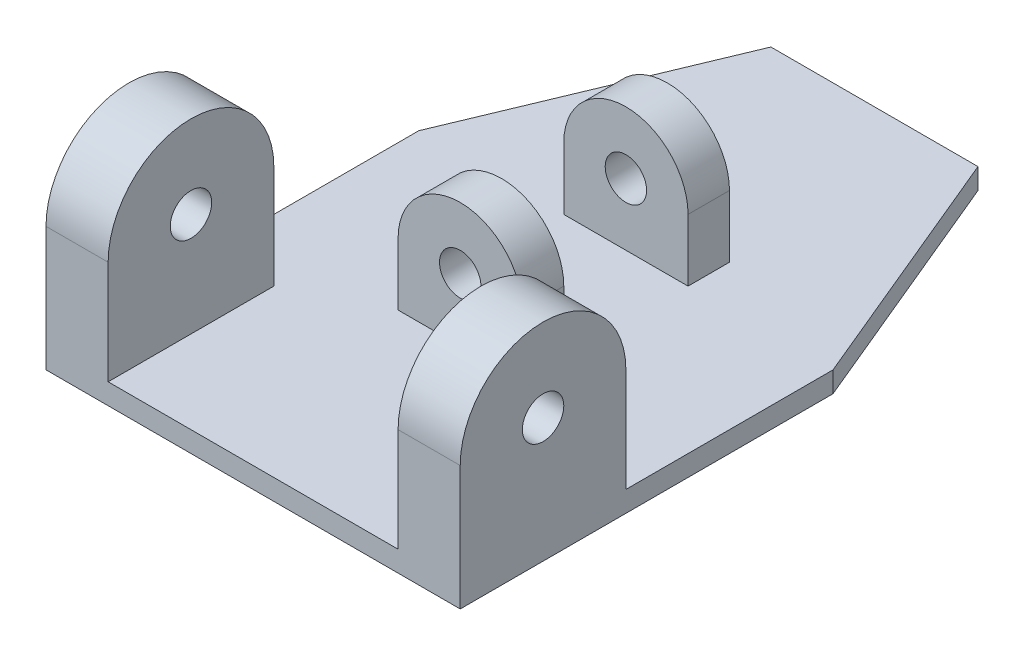
SolidWorks part; units mm, degrees
ref_plane "前视基准面" through (0, 0, 0) normal (0, 0, 1) x (1, 0, 0)
ref_plane "上视基准面" through (0, 0, 0) normal (0, 1, 0) x (1, 0, 0)
ref_plane "右视基准面" through (0, 0, 0) normal (1, 0, 0) x (0, 0, -1)
other "Configuration Table"
sketch "草图1" plane through (0, 0, 0) normal (0, 1, 0) x (1, 0, 0)
  line L0 (0, 0) -> (0, 255.8207) construction
  line L1 (-100, 0) -> (100, 0)
  line L2 (100, 0) -> (100, 180)
  line L3 (100, 180) -> (50, 300)
  line L4 (50, 300) -> (-50, 300)
  line L5 (-100, 180) -> (-50, 300)
  line L6 (-100, 0) -> (-100, 180)
  point P8 (0, 300)
  dimension "D1" = 300
  dimension "D2" = 100
  dimension "D3" = 120
  dimension "D4" = 50
extrude "凸台-拉伸1" add sketch "草图1" along normal blind 10
sketch "草图2" plane through (100, 0, 0) normal (1, 0, 0) x (0, 0, -1)
  line L0 (40, 100) -> (40, -10.3339) construction
  line L1 (0, 10) -> (0, 0) construction
  line L2 (0, 10) -> (0, 60)
  line L3 (80, 10) -> (80, 60)
  arc A0 (80, 60) -> (0, 60) centre (40, 60) ccw
  circle A1 centre (40, 60) radius 10
  line M6 (180, 10) -> (0, 10)
  dimension "D3" = 20
  dimension "D1" = 40
  dimension "D2" = 50
extrude "凸台-拉伸2" add sketch "草图2" against normal up to surface (200 mm away) contours A0 L0 A1 L3 M6 | L0 A0 L2 A1 M6 up to face at (-100, 5, -90)
sketch "草图3" plane through (0, 10, 0) normal (0, 1, 0) x (1, 0, 0)
  line L0 (0, 0) -> (0, 135.8056) construction
  line L1 (-100, 0) -> (100, 0) construction
  line L2 (-70, 0) -> (70, 0)
  line L3 (-70, 0) -> (-70, 100)
  line L4 (-70, 100) -> (70, 100)
  line L5 (70, 0) -> (70, 100)
  line L6 (100, 0) -> (100, 80) construction
  line L7 (-100, 80) -> (-100, 0) construction
  dimension "D1" = 30
  dimension "D2" = 30
  dimension "D3" = 100
extrude "切除-拉伸1" cut sketch "草图3" along normal blind 171
sketch "草图4" plane through (0, 0, 0) normal (0, 0, 1) x (1, 0, 0)
  line L0 (0, 0) -> (0, 92.3322) construction
  line L1 (30, 40) -> (30, 10)
  line L2 (-30, 40) -> (-30, 10)
  line L3 (-70, 10) -> (70, 10) construction
  arc A0 (-30, 40) -> (30, 40) centre (0, 40) cw
  circle A1 centre (0, 40) radius 10
  line M10 (70, 10) -> (-70, 10)
  dimension "D2" = 30
  dimension "D3" = 20
  dimension "D1" = 30
extrude "凸台-拉伸3" add sketch "草图4" against normal blind 100 from offset 100 contours L0 L1 A0 A1 M10 | L0 A1 A0 L2 M10 offset against normal yes
sketch "草图5" plane through (0, 10, 0) normal (0, 1, 0) x (1, 0, 0)
  line L0 (-47.074, 150) -> (51.1394, 150) construction
  line L1 (30, 200) -> (-30, 200) construction
  line L2 (30, 100) -> (-30, 100) construction
  line L3 (-30, 100) -> (30, 100) construction
  line L4 (-40, 180) -> (40, 180)
  line L5 (-40, 180) -> (-40, 120)
  line L6 (-40, 120) -> (40, 120)
  line L7 (40, 180) -> (40, 120)
  line L8 (30, 200) -> (30, 100) construction
  line L9 (-30, 200) -> (-30, 100) construction
  dimension "D1" = 20
  dimension "D2" = 20
  dimension "D3" = 10
  dimension "D4" = 10
extrude "切除-拉伸2" cut sketch "草图5" along normal blind 110 contours L7 L6 L5 L4
